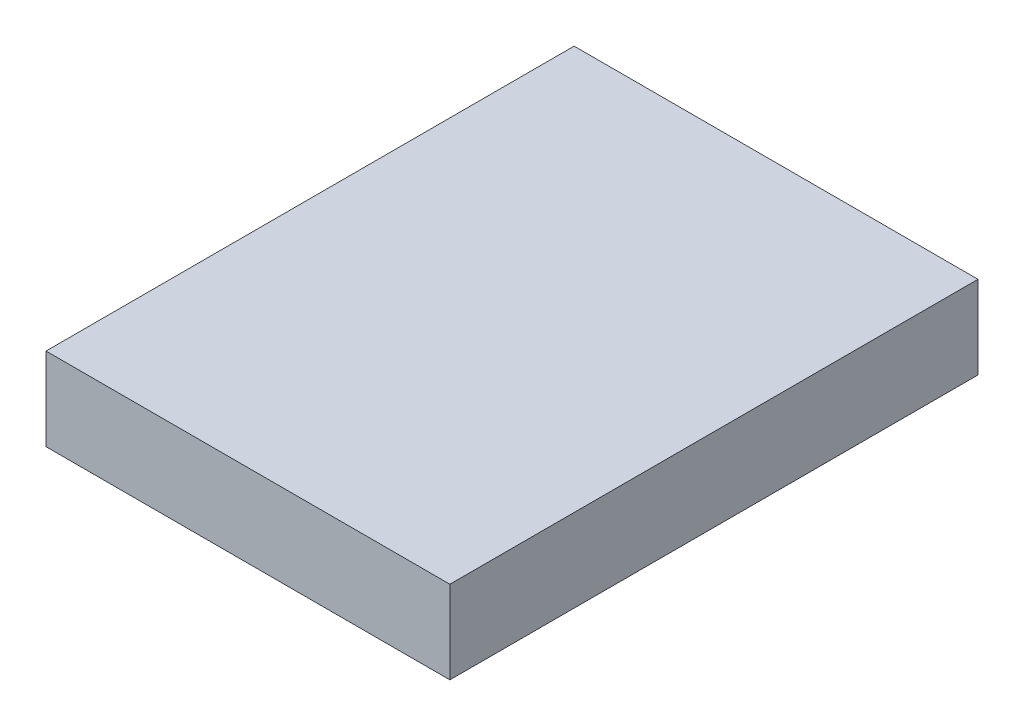
SolidWorks part; units mm, degrees
ref_plane "Front Plane" through (0, 0, 0) normal (0, 0, 1) x (1, 0, 0)
ref_plane "Top Plane" through (0, 0, 0) normal (0, 1, 0) x (1, 0, 0)
ref_plane "Right Plane" through (0, 0, 0) normal (1, 0, 0) x (0, 0, -1)
sketch "Sketch1" plane through (0, 0, 0) normal (0, 1, 0) x (1, 0, 0)
  line L1 (-19.5, 25.5) -> (19.5, 25.5)
  line L2 (-19.5, 25.5) -> (-19.5, -25.5)
  line L3 (-19.5, -25.5) -> (19.5, -25.5)
  line L4 (19.5, 25.5) -> (19.5, -25.5)
  line L5 (-19.5, 25.5) -> (19.5, -25.5) construction
  line L6 (-19.5, -25.5) -> (19.5, 25.5) construction
  point P0 (0, 0)
  dimension "D1" = 39
  dimension "D2" = 51
extrude "Boss-Extrude1" add sketch "Sketch1" along normal blind 8
sketch "Sketch2" plane through (0, 8, 0) normal (0, 1, 0) x (1, 0, 0)
  point P0 (0, 0)
